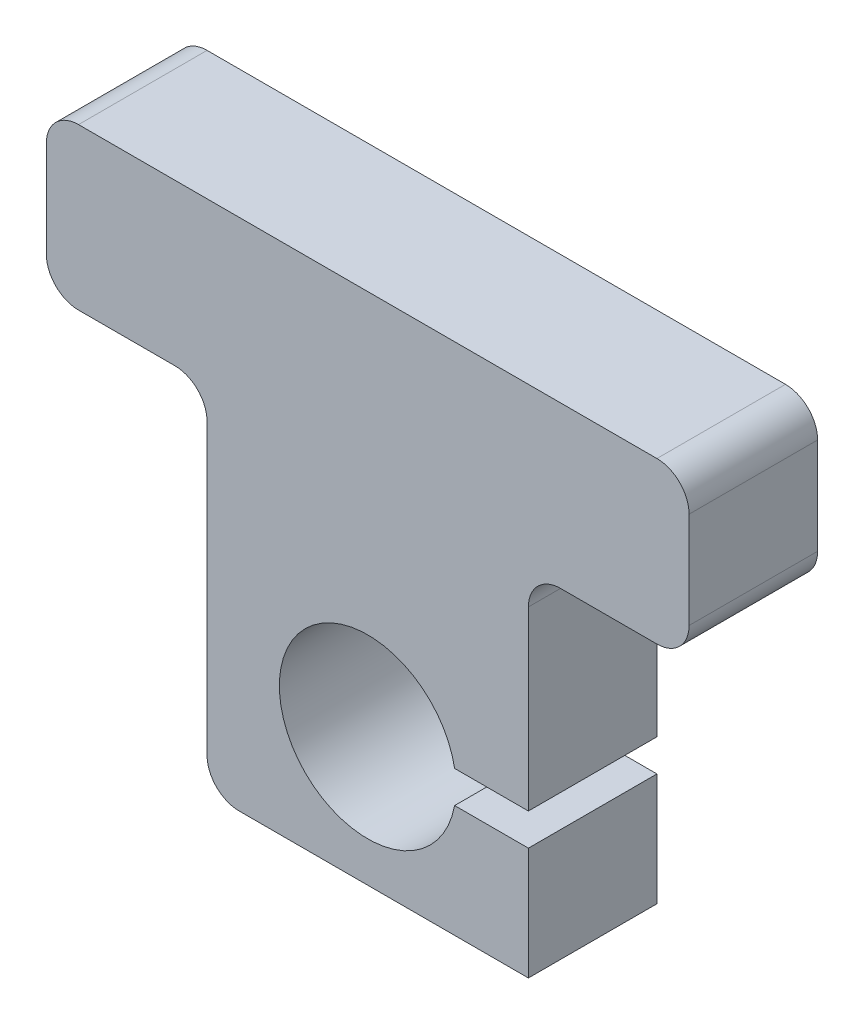
SolidWorks part; units mm, degrees
ref_plane "Front Plane" through (0, 0, 0) normal (0, 0, 1) x (1, 0, 0)
ref_plane "Top Plane" through (0, 0, 0) normal (0, 1, 0) x (1, 0, 0)
ref_plane "Right Plane" through (0, 0, 0) normal (1, 0, 0) x (0, 0, -1)
sketch "Sketch1" plane through (0, 0, 0) normal (0, 0, 1) x (1, 0, 0)
  line L0 (12, 14) -> (18, 14)
  line L1 (-8, -8) -> (10, -8)
  line L2 (-10, -6) -> (-10, 12)
  line L3 (0, 0) -> (21.2282, 0) construction
  line L4 (10, -8) -> (10, -1)
  line L5 (18, 24) -> (15, 24) construction
  line L6 (18, 24) -> (18, 14) construction
  line L7 (-18, 24) -> (18, 24)
  line L8 (-20, 22) -> (-20, 16)
  line L9 (-18, 14) -> (-12, 14)
  line L10 (20, 22) -> (20, 16)
  line L11 (-20, 24) -> (20, 14) construction
  line L12 (-20, 14) -> (20, 24) construction
  line L13 (18, 14) -> (15, 14) construction
  line L14 (15, 24) -> (15, 14) construction
  line L15 (10, 1) -> (10, 12)
  line L16 (5.4083, -1) -> (10, -1)
  line L18 (5.4083, 1) -> (10, 1)
  line L20 (4.2105, -1) -> (11.2281, 1) construction
  line L21 (4.2105, 1) -> (11.2281, -1) construction
  arc A0 (5.4083, 1) -> (5.4083, -1) centre (0, 0) ccw
  arc A1 (12, 14) -> (10, 12) centre (12, 12) ccw
  arc A2 (18, 14) -> (20, 16) centre (18, 16) ccw
  arc A3 (18, 24) -> (20, 22) centre (18, 22) cw
  arc A4 (-18, 24) -> (-20, 22) centre (-18, 22) ccw
  arc A5 (-20, 16) -> (-18, 14) centre (-18, 16) ccw
  arc A6 (-8, -8) -> (-10, -6) centre (-8, -6) cw
  arc A7 (-10, 12) -> (-12, 14) centre (-12, 12) ccw
  point P7 (0, 19)
  point P17 (7.7193, 0)
  point P41 (-10, -8)
  dimension "D1" = 11
  dimension "D10" = 2
  dimension "D2" = 20
  dimension "D3" = 14
  dimension "D4" = 10
  dimension "D5" = 8
  dimension "D6" = 10
  dimension "D7" = 20
  dimension "D8" = 3
  dimension "D9" = 2
extrude "Boss-Extrude1" add sketch "Sketch1" along normal blind 8
